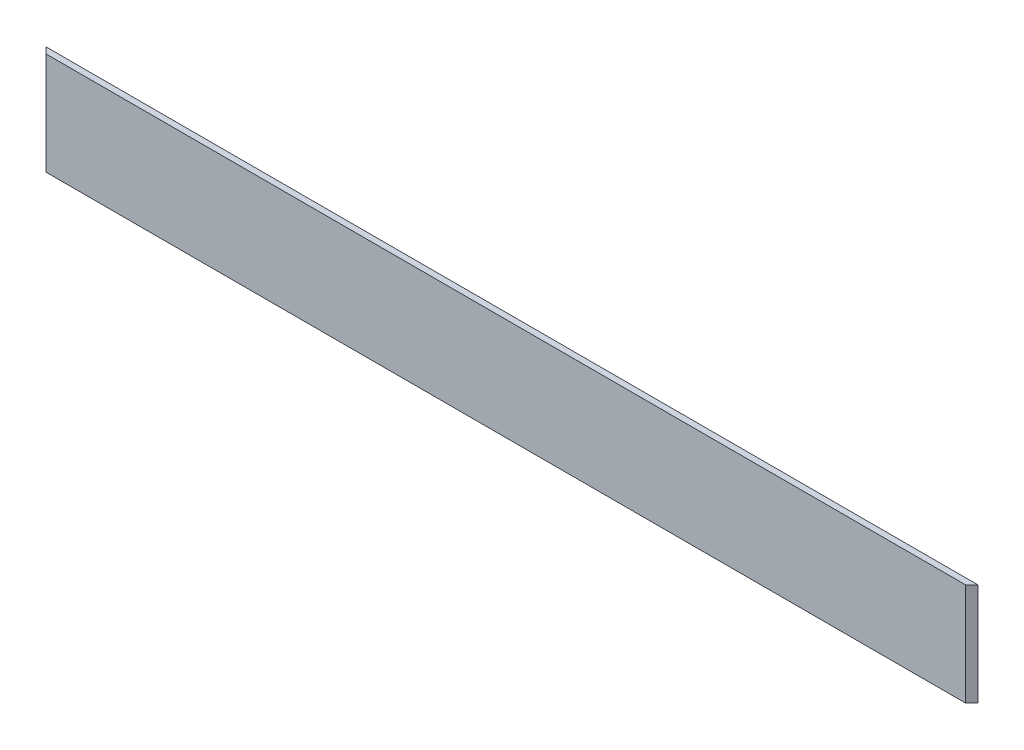
SolidWorks part; units mm, degrees
ref_plane "Front Plane" through (0, 0, 0) normal (0, 0, 1) x (1, 0, 0)
ref_plane "Top Plane" through (0, 0, 0) normal (0, 1, 0) x (1, 0, 0)
ref_plane "Right Plane" through (0, 0, 0) normal (1, 0, 0) x (0, 0, -1)
sketch "Sketch1" plane through (0, 0, 0) normal (0, 1, 0) x (1, 0, 0)
  line L1 (227.5, -1.5) -> (-227.5, -1.5)
  line L2 (227.5, -1.5) -> (227.5, 1.5)
  line L3 (227.5, 1.5) -> (-227.5, 1.5)
  line L4 (-227.5, -1.5) -> (-227.5, 1.5)
  line L5 (227.5, -1.5) -> (-227.5, 1.5) construction
  line L6 (227.5, 1.5) -> (-227.5, -1.5) construction
  point P0 (0, 0)
  dimension "D1" = 455
  dimension "D2" = 3
extrude "Boss-Extrude1" add sketch "Sketch1" along normal blind 50
sketch "Sketch2" plane through (0, 50, 0) normal (0, 1, 0) x (1, 0, 0)
  line L0 (-227.5, 1.5) -> (-227.5, -1.5)
  line L2 (-227.5, -1.5) -> (-224.5, -1.5)
  line L3 (-227.5, -1.5) -> (227.5, -1.5) construction
  line L4 (-224.5, -1.5) -> (-227.5, 1.5)
  line L5 (227.5, -1.5) -> (227.5, 1.5)
  line L7 (224.5, -1.5) -> (227.5, -1.5)
  line L8 (227.5, 1.5) -> (224.5, -1.5)
  dimension "D1" = 45
  dimension "D2" = 45
extrude "Cut-Extrude1" cut sketch "Sketch2" against normal through all
